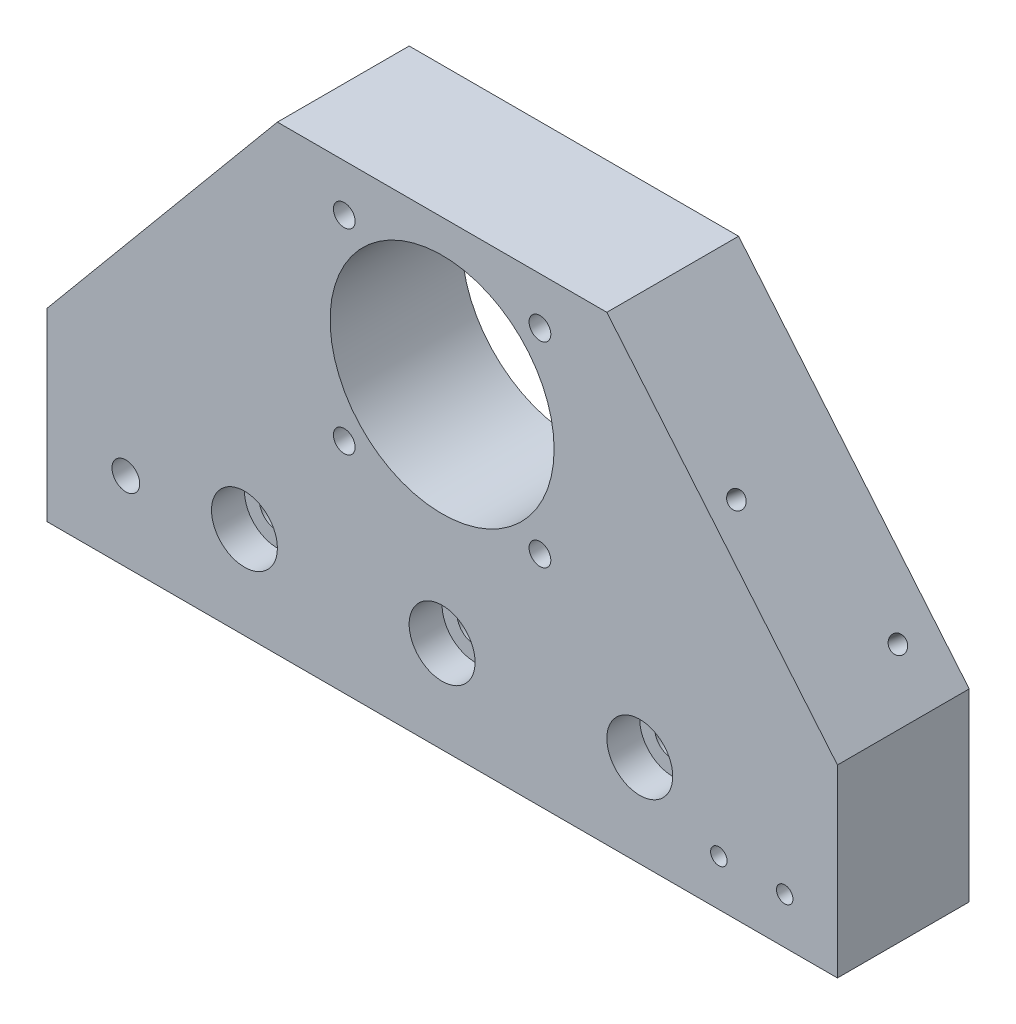
SolidWorks part; units mm, degrees
ref_plane "Front Plane" through (0, 0, 0) normal (0, 0, 1) x (1, 0, 0)
ref_plane "Top Plane" through (0, 0, 0) normal (0, 1, 0) x (1, 0, 0)
ref_plane "Right Plane" through (0, 0, 0) normal (1, 0, 0) x (0, 0, -1)
sketch "Sketch1" plane through (0, 0, 0) normal (0, 0, 1) x (1, 0, 0)
  line L0 (60, 0) -> (-60, 0)
  line L1 (-60, 0) -> (-60, 28)
  line L2 (-60, 28) -> (-25, 70)
  line L3 (-25, 70) -> (25, 70)
  line L4 (0, 0) -> (0, 70) construction
  line L5 (60, 28) -> (25, 70)
  line L6 (60, 0) -> (60, 28)
  dimension "D1" = 120
  dimension "D2" = 28
  dimension "D3" = 50
  dimension "D4" = 70
extrude "Boss-Extrude1" add sketch "Sketch1" along normal blind 20
sketch "Sketch2" plane through (0, 0, 20) normal (0, 0, 1) x (1, 0, 0)
  line L0 (0, 0) -> (0, 70) construction
  line L1 (-60, 0) -> (60, 0) construction
  line L2 (25, 70) -> (-25, 70) construction
  line L3 (-60, 14) -> (60, 14) construction
  line L4 (-60, 28) -> (-60, 0) construction
  line L5 (60, 0) -> (60, 28) construction
  point P12 (0, 14)
  point P13 (-30, 14)
  point P14 (30, 14)
  point P15 (0, 48)
  dimension "D1" = 30
hole_wizard "CBORE for M5 SHCS1" positions "3DSketch1" profile "Sketch3" counterbore size "M5" standard "ANSI Metric" end condition through all
sketch3d "3DSketch1"
  point P0 (-30, 14, 20)
  point P3 (0, 14, 20)
  point P6 (30, 14, 20)
sketch "Sketch3" plane through (-30, 14, 20) normal (1, 0, 0) x (0, -1, 0)
  line L0 (0, 0) -> (0, 20)
  line L1 (0, 20) -> (2.75, 20)
  line L3 (2.75, 20) -> (2.75, 5)
  line L4 (2.75, 5) -> (5, 5)
  line L5 (5, 5) -> (5, 0)
  line L7 (5, 0) -> (0, 0)
  line L11 (0, -6.35) -> (0, 107.95) construction
  dimension "Thru Hole Dia." = 5.5
  dimension "Thru Hole Depth" = 20
  dimension "C'Bore Dia." = 10
  dimension "C'Bore Depth" = 5
sketch "Sketch4" plane through (0, 0, 20) normal (0, 0, 1) x (1, 0, 0)
  circle A0 centre (0, 48) radius 17
  dimension "D1" = 34
extrude "Cut-Extrude1" cut sketch "Sketch4" against normal through all
sketch "Sketch5" plane through (0, 0, 20) normal (0, 0, 1) x (1, 0, 0)
  point P0 (14.8492, 33.1508)
  point P1 (-14.8492, 33.1508)
  point P2 (-14.8492, 62.8492)
  point P3 (14.8492, 62.8492)
hole_wizard "M4 Tapped Hole1" positions "3DSketch3" profile "Sketch7" tap size "M4" standard "ISO" end condition through all
sketch3d "3DSketch3"
  point P0 (-14.8492, 62.8492, 20)
  point P3 (14.8492, 62.8492, 20)
  point P6 (14.8492, 33.1508, 20)
  point P9 (-14.8492, 33.1508, 20)
sketch "Sketch7" plane through (-14.8492, 62.8492, 20) normal (1, 0, 0) x (0, -1, 0)
  line L0 (0, 0) -> (0, 20)
  line L1 (0, 20) -> (1.65, 20)
  line L2 (1.65, 20) -> (1.65, 0)
  line L5 (1.65, 0) -> (0, 0)
  line L11 (0, -6.35) -> (0, 107.95) construction
  dimension "Thread Major Dia." = 3.3
  dimension "Thru Tap Drill Depth" = 20
sketch "Sketch8" plane through (0, 0, 0) normal (0, -1, 0) x (1, 0, 0)
  line L0 (-20, 18.72) -> (-20, 0) construction
  line L1 (-60, 0) -> (60, 0) construction
  line L2 (20, 18.72) -> (20, 0) construction
  line L3 (-60, 10) -> (60, 10) construction
  line L4 (-60, 20) -> (-60, 0) construction
  line L5 (60, 20) -> (60, 0) construction
  line L6 (0, 0) -> (0, 20) construction
  point P12 (-20, 10)
  point P13 (20, 10)
  dimension "D1" = 20
  dimension "D2" = 20
hole_wizard "M4 Tapped Hole2" positions "Sketch10" profile "Sketch11" tap size "M4" standard "ISO"
sketch "Sketch10" plane through (0, 0, 0) normal (0, -1, 0) x (-1, 0, 0)
  point P0 (20, -10)
  point P3 (-20, -10)
sketch "Sketch11" plane through (-20, 0, 10) normal (1, 0, 0) x (0, 0, -1)
  line L0 (0, 0) -> (0, 15.9914)
  line L1 (0, 15.9914) -> (1.65, 15)
  line L2 (1.65, 15) -> (1.65, 0)
  line L5 (1.65, 0) -> (0, 0)
  line L10 (0, 15.9914) -> (-1.65, 15) construction
  line L11 (0, -6.35) -> (0, 107.95) construction
  dimension "Tap Drill Dia." = 3.3
  dimension "Tap Drill Depth" = 15
  dimension "Drill Angle" = 118
sketch "Sketch12" plane through (0, 0, 20) normal (0, 0, 1) x (1, 0, 0)
  line L0 (60, 0) -> (60, 28) construction
  line L2 (47, 0) -> (47, 14) construction
  line L3 (52, 7) -> (42, 7) construction
  line L5 (-60, 0) -> (60, 0) construction
  line L6 (-60, 14) -> (60, 14) construction
  point P9 (42, 7)
  point P10 (52, 7)
  dimension "D1" = 13
  dimension "D2" = 7
  dimension "D3" = 5
hole_wizard "M3 Tapped Hole1" positions "3DSketch5" profile "Sketch14" tap size "M3" standard "ISO"
sketch3d "3DSketch5"
  point P0 (42, 7, 20)
  point P3 (52, 7, 20)
sketch "Sketch14" plane through (42, 7, 20) normal (1, 0, 0) x (0, -1, 0)
  line L0 (0, 0) -> (0, 8.2511)
  line L1 (0, 8.2511) -> (1.25, 7.5)
  line L2 (1.25, 7.5) -> (1.25, 0)
  line L5 (1.25, 0) -> (0, 0)
  line L10 (0, 8.2511) -> (-1.25, 7.5) construction
  line L11 (0, -6.35) -> (0, 107.95) construction
  dimension "Tap Drill Dia." = 2.5
  dimension "Tap Drill Depth" = 7.5
  dimension "Drill Angle" = 118
sketch "Sketch15" plane through (49.1803, 40.9836, 0) normal (0.7682, 0.6402, 0) x (0, 0, -1)
  line L1 (-20, 0) -> (-20, 53.7755) construction
  line L2 (-20, -16.9009) -> (0, -16.9009) construction
  point P0 (-5.7, -8.9009)
  point P1 (-16, 13.2991)
  dimension "D1" = 22.2
  dimension "D2" = 10.3
  dimension "D3" = 4
  dimension "D4" = 8
hole_wizard "M3 Tapped Hole2" positions "Sketch17" profile "Sketch16" tap size "M3" standard "ISO"
sketch "Sketch17" plane through (49.1803, 40.9836, 0) normal (0.7682, 0.6402, 0) x (0, 0, -1)
  point P0 (-16, 13.2991)
  point P3 (-5.7, -8.9009)
sketch "Sketch16" plane through (40.6664, 51.2003, 16) normal (0, 0, 1) x (-0.6402, 0.7682, 0)
  line L0 (0, 0) -> (0, 12.2511)
  line L1 (0, 12.2511) -> (1.25, 11.5)
  line L2 (1.25, 11.5) -> (1.25, 0)
  line L5 (1.25, 0) -> (0, 0)
  line L10 (0, 12.2511) -> (-1.25, 11.5) construction
  line L11 (0, -6.35) -> (0, 107.95) construction
  dimension "Tap Drill Dia." = 2.5
  dimension "Tap Drill Depth" = 11.5
  dimension "Drill Angle" = 118
sketch "Sketch18" plane through (0, 0, 20) normal (0, 0, 1) x (1, 0, 0)
  line L0 (-60, 0) -> (60, 0) construction
  line L1 (-60, 28) -> (-60, 0) construction
  point P0 (-48, 12)
  dimension "D1" = 12
  dimension "D2" = 12
hole_wizard "M5 Tapped Hole1" positions "Sketch21" profile "Sketch20" tap size "M5" standard "ISO" end condition through all
sketch "Sketch21" plane through (0, 0, 20) normal (0, 0, 1) x (1, 0, 0)
  point P0 (-48, 12)
sketch "Sketch20" plane through (-48, 12, 20) normal (1, 0, 0) x (0, -1, 0)
  line L0 (0, 0) -> (0, 20)
  line L1 (0, 20) -> (2.1, 20)
  line L2 (2.1, 20) -> (2.1, 0)
  line L5 (2.1, 0) -> (0, 0)
  line L11 (0, -6.35) -> (0, 107.95) construction
  dimension "Thread Major Dia." = 4.2
  dimension "Thru Tap Drill Depth" = 20
